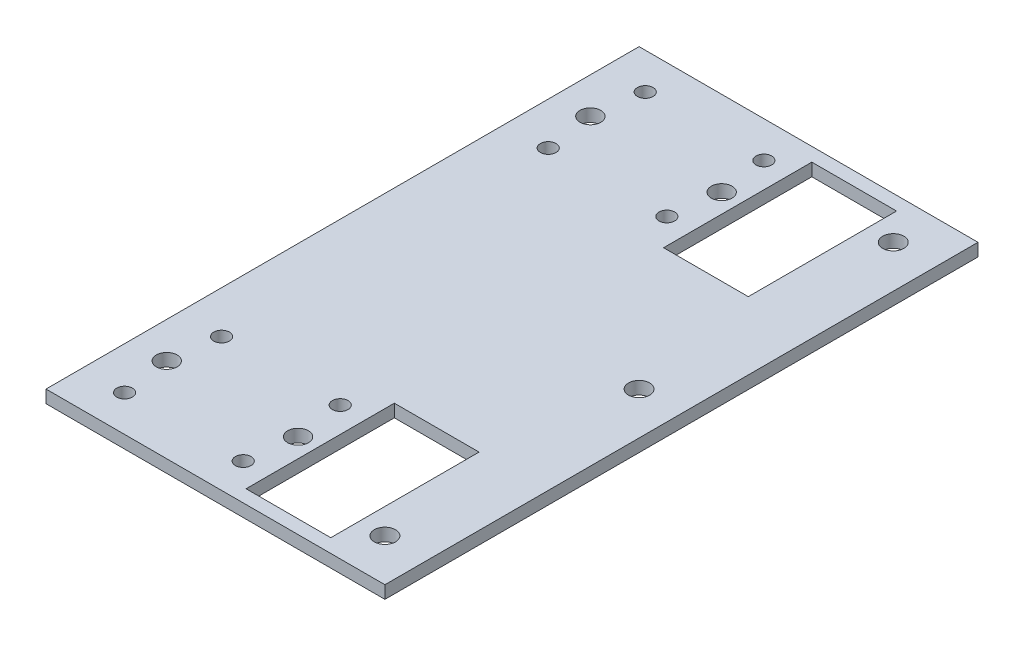
SolidWorks part; units mm, degrees
ref_plane "前视基准面" through (0, 0, 0) normal (0, 0, 1) x (1, 0, 0)
ref_plane "上视基准面" through (0, 0, 0) normal (0, 1, 0) x (1, 0, 0)
ref_plane "右视基准面" through (0, 0, 0) normal (1, 0, 0) x (0, 0, -1)
other "Configuration Table"
sketch "草图1" plane through (0, 0, 0) normal (0, 1, 0) x (1, 0, 0)
  line L0 (-40, 0) -> (49960, 0) construction
  line L1 (-40, -70) -> (40, -70)
  line L2 (-40, -70) -> (-40, 70)
  line L3 (-40, 70) -> (40, 70)
  line L4 (40, -70) -> (40, 70)
  line L5 (-40, -70) -> (40, 70) construction
  line L6 (-40, 70) -> (40, -70) construction
  line L7 (-40, 70) -> (8, 70)
  line L8 (-40, 70) -> (-40, 30)
  line L9 (-40, 30) -> (8, 30)
  line L10 (8, 70) -> (8, 30)
  line L11 (-40, -70) -> (8, -70)
  line L12 (-40, -70) -> (-40, -30)
  line L13 (-40, -30) -> (8, -30)
  line L14 (8, -70) -> (8, -30)
  line L15 (-40, 70) -> (-30, 70)
  line L16 (-40, 70) -> (-40, 61.45)
  line L17 (-40, 61.45) -> (-30, 61.45)
  line L18 (-30, 70) -> (-30, 61.45)
  line L19 (-16, 30) -> (-16, 50030) construction
  line L20 (8, 50) -> (-0.5, 50) construction
  line L22 (40, 70) -> (30, 70)
  line L23 (40, 70) -> (40, 60)
  line L24 (40, 60) -> (30, 60)
  line L25 (30, 70) -> (30, 60)
  circle A0 centre (-30, 61.45) radius 1.85
  circle A1 centre (-2, 61.45) radius 1.85
  circle A2 centre (-2, 38.55) radius 1.85
  circle A3 centre (-30, 38.55) radius 1.85
  circle A4 centre (-0.5, 50) radius 2.45
  circle A5 centre (-31.5, 50) radius 2.45
  circle A6 centre (-2, -38.55) radius 1.85
  circle A7 centre (-0.5, -50) radius 2.45
  circle A8 centre (-2, -61.45) radius 1.85
  circle A9 centre (-30, -38.55) radius 1.85
  circle A10 centre (-31.5, -50) radius 2.45
  circle A11 centre (-30, -61.45) radius 1.85
  circle A12 centre (30, 60) radius 2.5
  circle A13 centre (30, 0) radius 2.5
  circle A14 centre (30, -60) radius 2.5
  point P0 (0, 0)
  point P21 (-16, 30)
  point P33 (-40, 0)
  dimension "D9" = 3.7
  dimension "D11" = 4.9
  dimension "D14" = 5
  dimension "D1" = 80
  dimension "D2" = 140
  dimension "D3" = 40
  dimension "D4" = 48
  dimension "D5" = 48
  dimension "D6" = 40
  dimension "D7" = 10
  dimension "D8" = 8.55
  dimension "D10" = 8.5
  dimension "D12" = 10
  dimension "D13" = 10
  dimension "D15" = 3
extrude "凸台-拉伸1" add sketch "草图1" along normal blind 3 contours A12 L25 L3 L10 L9 L2 L13 L14 L1 L4 L24 A14 A13 | A12 L24 L4 L3 L25 | A0 L17 L2 L9 L10 L7 L18 A3 A2 A1 A4 A5 | A0 L18 L3 L8 L17 | L1 L14 L13 L2 A7 A6 A8 A9 A10 A11
sketch "草图2" plane through (0, 3, 0) normal (0, 1, 0) x (1, 0, 0)
  line L5 (-1000, 0) -> (49000, 0) construction
  line L6 (4, 66.775) -> (24, 66.775)
  line L7 (4, -31.775) -> (24, -31.775)
  line L8 (4, -31.775) -> (4, -66.775)
  line L9 (4, -66.775) -> (24, -66.775)
  line L10 (24, -31.775) -> (24, -66.775)
  line L11 (4, -31.775) -> (24, -66.775) construction
  line L12 (4, -66.775) -> (24, -31.775) construction
  line L13 (4, 31.775) -> (4, 66.775)
  line L14 (24, 31.775) -> (24, 66.775)
  line L15 (4, 31.775) -> (24, 31.775)
  point P6 (14, -49.275)
  dimension "D1" = 35
  dimension "D2" = 20
extrude "切除-拉伸1" cut sketch "草图2" against normal blind 10
